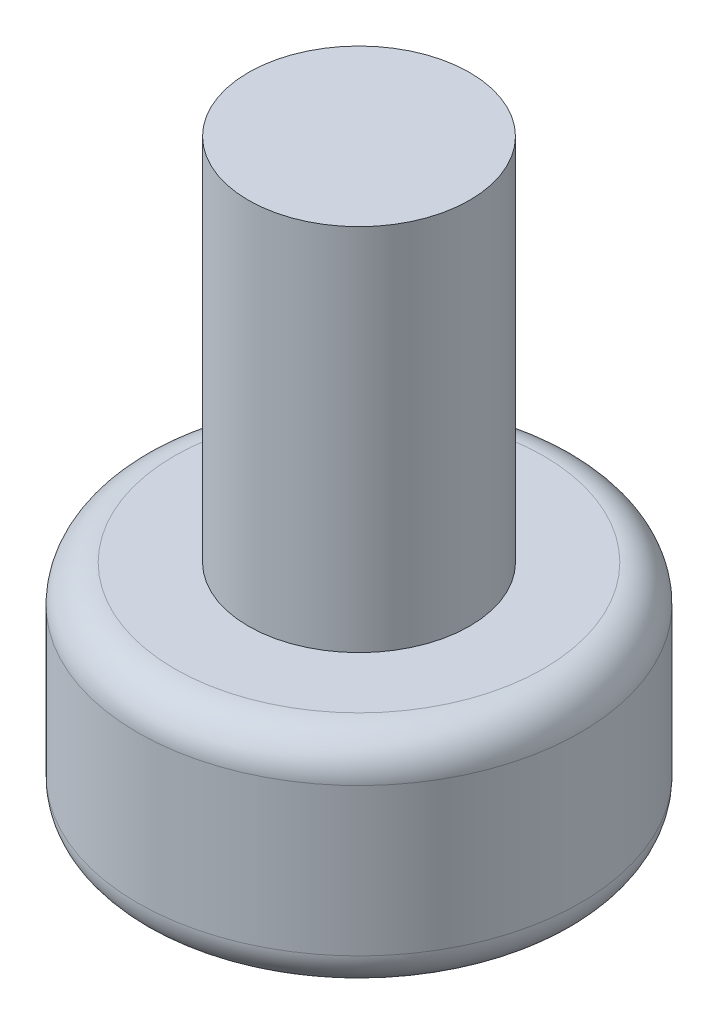
SolidWorks part; units mm, degrees
ref_plane "Ön Düzlem" through (0, 0, 0) normal (0, 0, 1) x (1, 0, 0)
ref_plane "Üst Düzlem" through (0, 0, 0) normal (0, 1, 0) x (1, 0, 0)
ref_plane "Sağ Düzlem" through (0, 0, 0) normal (1, 0, 0) x (0, 0, -1)
sketch "Çizim1" plane through (0, 0, 0) normal (0, 1, 0) x (1, 0, 0)
  circle A0 centre (0, 0) radius 3
  dimension "D1" = 6
extrude "Yükseklik-Ekstrüzyon1" add sketch "Çizim1" along normal blind 3
sketch "Çizim2" plane through (0, 3, 0) normal (0, 1, 0) x (1, 0, 0)
  circle A0 centre (0, 0) radius 1.5
  dimension "D1" = 3
extrude "Yükseklik-Ekstrüzyon2" add sketch "Çizim2" along normal blind 5
fillet "Radyus1" radius 0.5 2 edges at (0, 0, 3) (0, 3, 3)
sketch "Çizim3" plane through (0, 0, 0) normal (0, -1, 0) x (1, 0, 0)
  line L1 (1.7321, 0) -> (0.866, 1.5)
  line L2 (0.866, 1.5) -> (-0.866, 1.5)
  line L3 (-0.866, 1.5) -> (-1.7321, 0)
  line L4 (-1.7321, 0) -> (-0.866, -1.5)
  line L5 (-0.866, -1.5) -> (0.866, -1.5)
  line L6 (0.866, -1.5) -> (1.7321, 0)
  circle A0 centre (0, 0) radius 1.5 construction
  point P1 (1.299, -0.75)
  dimension "D1" = 3
extrude "Kes-Ekstrüzyon1" cut sketch "Çizim3" against normal blind 2
sketch "Çizim9" plane through (0, 8, 0) normal (0, 1, 0) x (1, 0, 0)
  line L0 (0, 0) -> (-4.0156, 0) construction
